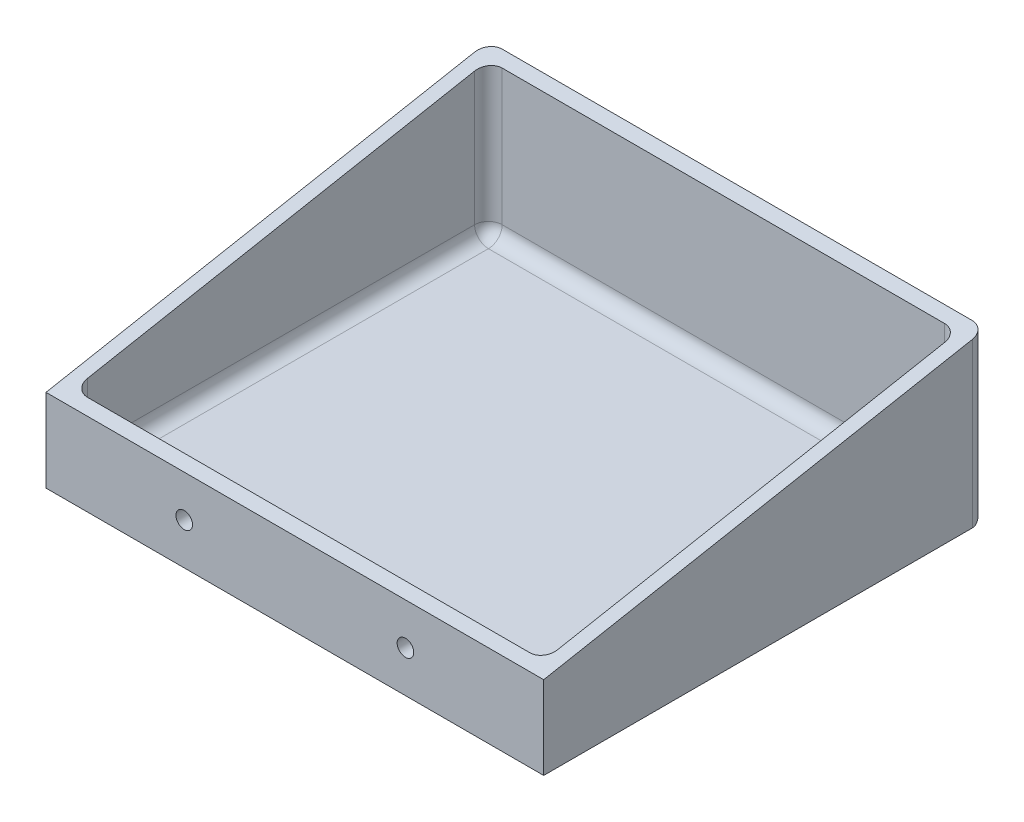
SolidWorks part; units mm, degrees
ref_plane "Front Plane" through (0, 0, 0) normal (0, 0, 1) x (1, 0, 0)
ref_plane "Top Plane" through (0, 0, 0) normal (0, 1, 0) x (1, 0, 0)
ref_plane "Right Plane" through (0, 0, 0) normal (1, 0, 0) x (0, 0, -1)
sketch "Sketch2" plane through (0, 0, 0) normal (1, 0, 0) x (0, 0, -1)
  line L0 (0, 0) -> (80, 0)
  line L1 (80, 0) -> (80, 30)
  line L2 (80, 30) -> (0, 15)
  line L3 (0, 15) -> (0, 0)
  dimension "D1" = 80
  dimension "D2" = 30
  dimension "D3" = 15
extrude "Boss-Extrude1" add sketch "Sketch2" along normal blind 90
shell "Shell1" thickness 2.5
fillet "Fillet1" radius 2.5 11 edges at (45, 2.5, -77.5) (87.5, 2.5, -40) (45, 2.5, -2.5) (2.5, 2.5, -40) (87.5, 8.9844, -2.5) (2.5, 8.9844, -2.5) (2.5, 16.0156, -77.5) (0, 15, -80) (87.5, 16.0156, -77.5) (90, 15, -80) (45, 0, -80)
sketch "Sketch3" plane through (0, 0, 0) normal (0, 0, 1) x (1, 0, 0)
  line L1 (90, 0) -> (0, 0) construction
  line L2 (0, 15) -> (0, 0) construction
  line L3 (90, 15) -> (90, 0) construction
  point P0 (25, 7.5)
  point P1 (65, 7.5)
  dimension "D1" = 7.5
  dimension "D2" = 7.5
  dimension "D3" = 40
  dimension "D4" = 25
  dimension "D5" = 25
hole_wizard "Ø3.0mm Dowel Hole1" positions "Sketch3" profile "Sketch5" hole size "Ø3.0" standard "ANSI Metric"
sketch "Sketch5" plane through (25, 7.5, 0) normal (1, 0, 0) x (0, -1, 0)
  line L0 (0, 0) -> (0, 2.5)
  line L1 (0, 2.5) -> (1.5, 2.5)
  line L2 (1.5, 2.5) -> (1.5, 0)
  line L5 (1.5, 0) -> (0, 0)
  line L11 (0, -6.35) -> (0, 107.95) construction
  dimension "Thru Hole Dia." = 3
  dimension "Thru Hole Depth" = 2.5
